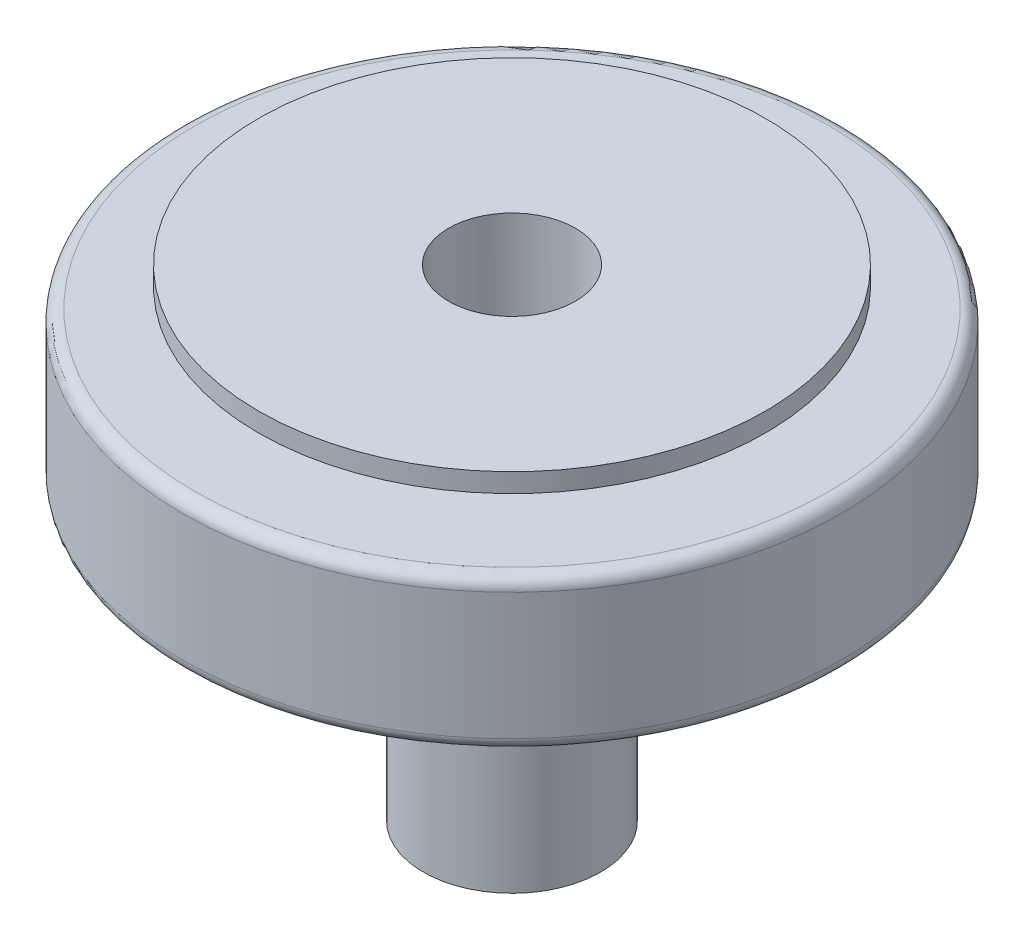
SolidWorks part; units mm, degrees
ref_plane "前视基准面" through (0, 0, 0) normal (0, 0, 1) x (1, 0, 0)
ref_plane "上视基准面" through (0, 0, 0) normal (0, 1, 0) x (1, 0, 0)
ref_plane "右视基准面" through (0, 0, 0) normal (1, 0, 0) x (0, 0, -1)
other "Configuration Table"
sketch "草图1" plane through (0, 0, 0) normal (0, 1, 0) x (1, 0, 0)
  circle A0 centre (0, 0) radius 26
  dimension "D1" = 52
extrude "凸台-拉伸1" add sketch "草图1" along normal blind 12
sketch "草图2" plane through (0, 12, 0) normal (0, 1, 0) x (1, 0, 0)
  circle A0 centre (0, 0) radius 17.5
  dimension "D1" = 35
extrude "凸台-拉伸2" add sketch "草图2" along normal blind 1.5
sketch "草图3" plane through (0, 0, 0) normal (0, -1, 0) x (1, 0, 0)
  circle A0 centre (0, 0) radius 17.5
  dimension "D1" = 35
extrude "凸台-拉伸3" add sketch "草图3" along normal blind 1.5
sketch "草图4" plane through (0, 13.5, 0) normal (0, 1, 0) x (1, 0, 0)
  circle A0 centre (0, 0) radius 20
  dimension "D1" = 40
extrude "凸台-拉伸4" add sketch "草图4" along normal blind 1.5
sketch "草图5" plane through (0, -1.5, 0) normal (0, -1, 0) x (1, 0, 0)
  circle A0 centre (0, 0) radius 20
  dimension "D1" = 40
extrude "凸台-拉伸5" add sketch "草图5" along normal blind 1.5
sketch "草图6" plane through (0, -3, 0) normal (0, -1, 0) x (1, 0, 0)
  circle A0 centre (0, 0) radius 5
  dimension "D1" = 10
extrude "切除-拉伸1" cut sketch "草图6" against normal through all
sketch "草图7" plane through (0, -3, 0) normal (0, -1, 0) x (1, 0, 0)
  circle A0 centre (0, 0) radius 7
  circle A1 centre (0, 0) radius 5
  dimension "D1" = 14
extrude "凸台-拉伸6" add sketch "草图7" along normal blind 20
sketch "草图8" plane through (0, 0, 0) normal (1, 0, 0) x (0, 0, -1)
  line L0 (0, -23) -> (0, -13)
  line L1 (-7, -23) -> (7, -23) construction
  circle A0 centre (0, -13) radius 2
  dimension "D2" = 4
  dimension "D1" = 10
extrude "切除-拉伸2" cut sketch "草图8" against normal through all
sketch "草图9" plane through (0, 0, 0) normal (0, 0, 1) x (1, 0, 0)
  line L0 (0, -23) -> (0, -13)
  line L1 (-7, -23) -> (7, -23) construction
  circle A0 centre (0, -13) radius 2
  dimension "D2" = 4
  dimension "D1" = 10
extrude "切除-拉伸3" cut sketch "草图9" against normal through all
fillet "圆角1" radius 1 1 edges at (0, 12, 26)
fillet "圆角2" radius 1 1 edges at (0, 0, 26)
sketch "草图11" plane through (0, 0, 0) normal (0, -1, 0) x (1, 0, 0)
  circle A1 centre (0, 0) radius 25
  circle A2 centre (0, 0) radius 25
  dimension "D1" = 0
sketch "草图13" plane through (0, 12, 0) normal (0, 1, 0) x (1, 0, 0)
  circle A1 centre (0, 0) radius 25
  circle A2 centre (0, 0) radius 25
  dimension "D1" = 0
curve "螺旋线/涡状线1" pitch 50 height 12.5 turns 0.25
ref_plane "基准面1" through (0, 12, 25) normal (-0.9529, -0.3033, 0) x (0, 0, 1)
